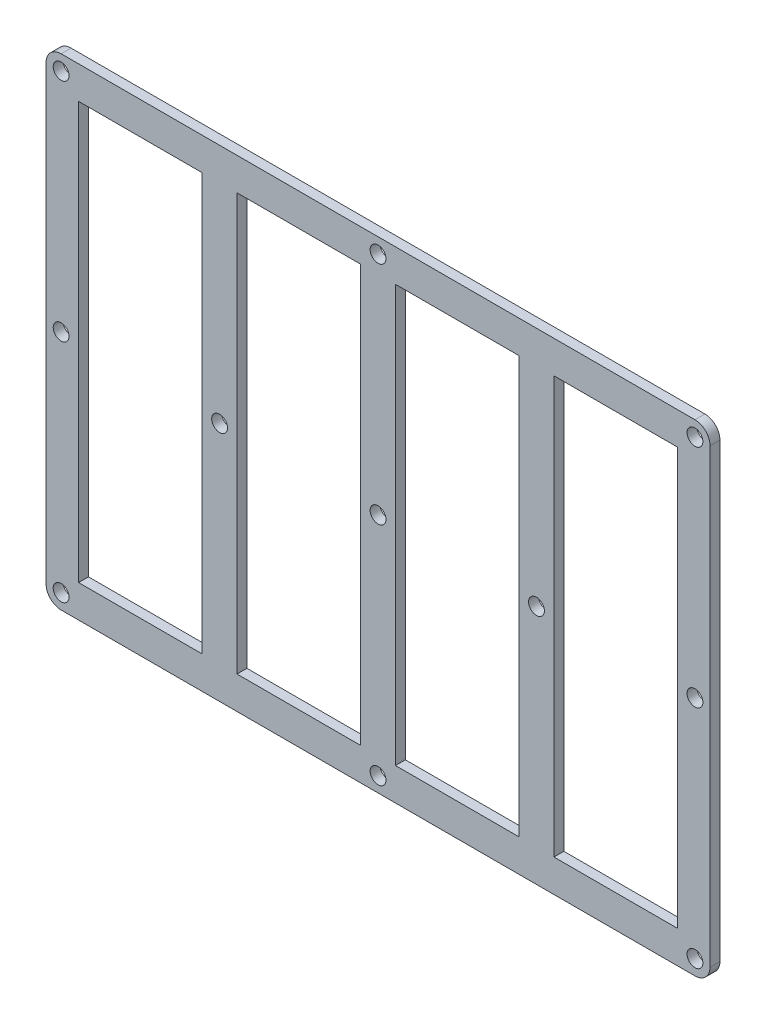
SolidWorks part; units mm, degrees
ref_plane "Front Plane" through (0, 0, 0) normal (0, 0, 1) x (1, 0, 0)
ref_plane "Top Plane" through (0, 0, 0) normal (0, 1, 0) x (1, 0, 0)
ref_plane "Right Plane" through (0, 0, 0) normal (1, 0, 0) x (0, 0, -1)
sketch "Sketch1" plane through (0, 0, 0) normal (0, 0, 1) x (1, 0, 0)
  line L0 (-152.4, 127) -> (-76.2, 127) construction
  line L1 (-152.4, 152.4) -> (152.4, 152.4)
  line L2 (-152.4, 152.4) -> (-152.4, -152.4)
  line L3 (-152.4, -152.4) -> (152.4, -152.4)
  line L4 (152.4, 152.4) -> (152.4, -152.4)
  line L5 (-76.2, 127) -> (-25.4, 127) construction
  line L6 (-25.4, 127) -> (25.4, 127) construction
  line L7 (25.4, 127) -> (76.2, 127) construction
  line L8 (76.2, 127) -> (152.4, 127) construction
  line L9 (-152.4, 0) -> (152.4, 0) construction
  line L10 (0, 152.4) -> (0, -152.4) construction
  line L11 (-118.11, 152.4) -> (-118.11, -152.4) construction
  line L12 (-152.4, -127) -> (152.4, -127) construction
  line L13 (127, 152.4) -> (127, -152.4) construction
  line L14 (-50.8, 152.4) -> (-50.8, -152.4) construction
  line L15 (50.8, 152.4) -> (50.8, -152.4) construction
  line L16 (-101.6, 152.4) -> (-101.6, -152.4) construction
  line L17 (-95.25, 66.04) -> (-57.15, 66.04) construction
  line L18 (-95.25, 66.04) -> (-95.25, -66.04) construction
  line L19 (-95.25, -66.04) -> (-57.15, -66.04) construction
  line L20 (-57.15, 66.04) -> (-57.15, -66.04) construction
  line L21 (-44.45, 66.04) -> (-6.35, 66.04) construction
  line L22 (-44.45, 66.04) -> (-44.45, -66.04) construction
  line L23 (-44.45, -66.04) -> (-6.35, -66.04) construction
  line L24 (-6.35, 66.04) -> (-6.35, -66.04) construction
  line L25 (6.35, 66.04) -> (44.45, 66.04) construction
  line L26 (6.35, 66.04) -> (6.35, -66.04) construction
  line L27 (6.35, -66.04) -> (44.45, -66.04) construction
  line L28 (44.45, 66.04) -> (44.45, -66.04) construction
  line L29 (57.15, 66.04) -> (95.25, 66.04) construction
  line L30 (57.15, 66.04) -> (57.15, -66.04) construction
  line L31 (57.15, -66.04) -> (95.25, -66.04) construction
  line L32 (95.25, 66.04) -> (95.25, -66.04) construction
  line L33 (101.6, 152.4) -> (101.6, -152.4) construction
  line L34 (-152.4, 120.65) -> (152.4, 120.65) construction
  line L35 (-101.6, 39.7057) -> (-95.25, 39.7057) construction
  line L36 (-57.15, 39.7057) -> (-50.8, 39.7057) construction
  line L37 (-76.2, 66.04) -> (-76.2, 0) construction
  line L38 (-76.2, 0) -> (-76.2, -66.04) construction
  line L39 (-152.4, 72.39) -> (152.4, 72.39) construction
  line L40 (-152.4, -72.39) -> (152.4, -72.39) construction
  line L41 (-76.2, 66.04) -> (-76.2, 72.39) construction
  line L42 (-95.25, -66.04) -> (-95.25, -72.39) construction
  line L43 (95.25, 39.7057) -> (101.6, 39.7057) construction
  line L44 (-95.25, 111.76) -> (-57.15, 111.76) construction
  line L45 (-57.15, 111.76) -> (-57.15, 118.4779) construction
  line L46 (-94.0266, 120.65) -> (-78.1749, 130.2582) construction
  line L47 (-95.25, 111.76) -> (-95.25, 118.4779) construction
  line L48 (-58.3734, 120.65) -> (-74.2251, 130.2582) construction
  line L49 (-107.3169, 130.81) -> (-83.1894, 130.81) construction
  line L50 (-6.35, 111.76) -> (-6.35, 118.4779) construction
  line L51 (-7.5734, 120.65) -> (-23.4251, 130.2582) construction
  line L52 (-43.2266, 120.65) -> (-27.3749, 130.2582) construction
  line L53 (-44.45, 111.76) -> (-44.45, 118.4779) construction
  line L54 (-6.35, 111.76) -> (-44.45, 111.76) construction
  line L55 (44.45, 111.76) -> (44.45, 118.4779) construction
  line L56 (43.2266, 120.65) -> (27.3749, 130.2582) construction
  line L57 (7.5734, 120.65) -> (23.4251, 130.2582) construction
  line L58 (6.35, 111.76) -> (6.35, 118.4779) construction
  line L59 (6.35, 111.76) -> (44.45, 111.76) construction
  line L60 (95.25, 111.76) -> (57.15, 111.76) construction
  line L61 (95.25, 111.76) -> (95.25, 118.4779) construction
  line L62 (94.0266, 120.65) -> (78.1749, 130.2582) construction
  line L63 (58.3734, 120.65) -> (74.2251, 130.2582) construction
  line L64 (57.15, 111.76) -> (57.15, 118.4779) construction
  line L65 (-95.25, -111.76) -> (-95.25, -118.4779) construction
  line L66 (-94.0266, -120.65) -> (-78.1749, -130.2582) construction
  line L67 (-58.3734, -120.65) -> (-74.2251, -130.2582) construction
  line L68 (-95.25, -111.76) -> (-57.15, -111.76) construction
  line L69 (-57.15, -111.76) -> (-57.15, -118.4779) construction
  line L70 (-44.45, -111.76) -> (-44.45, -118.4779) construction
  line L71 (-43.2266, -120.65) -> (-27.3749, -130.2582) construction
  line L72 (-6.35, -111.76) -> (-44.45, -111.76) construction
  line L73 (-7.5734, -120.65) -> (-23.4251, -130.2582) construction
  line L74 (-6.35, -111.76) -> (-6.35, -118.4779) construction
  line L75 (6.35, -111.76) -> (6.35, -118.4779) construction
  line L76 (7.5734, -120.65) -> (23.4251, -130.2582) construction
  line L77 (43.2266, -120.65) -> (27.3749, -130.2582) construction
  line L78 (6.35, -111.76) -> (44.45, -111.76) construction
  line L79 (44.45, -111.76) -> (44.45, -118.4779) construction
  line L80 (57.15, -111.76) -> (57.15, -118.4779) construction
  line L81 (58.3734, -120.65) -> (74.2251, -130.2582) construction
  line L82 (94.0266, -120.65) -> (78.1749, -130.2582) construction
  line L83 (95.25, -111.76) -> (57.15, -111.76) construction
  line L84 (95.25, -111.76) -> (95.25, -118.4779) construction
  line L85 (-152.4, 97.79) -> (152.4, 97.79) construction
  line L86 (-50.8, 39.7057) -> (-44.45, 39.7057) construction
  line L87 (-127, 152.4) -> (-127, -152.4) construction
  line L89 (-95.25, 101.6) -> (-92.3192, 101.6) construction
  line L90 (-95.25, 101.6) -> (-95.25, -101.6) construction
  line L96 (-90.8538, 101.6) -> (-90.8538, 68.58) construction
  line L97 (-89.3885, 101.6) -> (-89.3885, 68.58) construction
  line L98 (-92.3192, 101.6) -> (-92.3192, 68.58) construction
  line L99 (-83.5269, 101.6) -> (-83.5269, 68.58) construction
  line L100 (-86.4577, 101.6) -> (-86.4577, 68.58) construction
  line L101 (-89.3885, 101.6) -> (-86.4577, 101.6) construction
  line L102 (-77.6654, 101.6) -> (-77.6654, 68.58) construction
  line L103 (-80.5962, 101.6) -> (-80.5962, 68.58) construction
  line L104 (-83.5269, 101.6) -> (-80.5962, 101.6) construction
  line L105 (-71.8038, 101.6) -> (-71.8038, 68.58) construction
  line L106 (-74.7346, 101.6) -> (-74.7346, 68.58) construction
  line L107 (-77.6654, 101.6) -> (-74.7346, 101.6) construction
  line L108 (-65.9423, 101.6) -> (-65.9423, 68.58) construction
  line L109 (-68.8731, 101.6) -> (-68.8731, 68.58) construction
  line L110 (-71.8038, 101.6) -> (-68.8731, 101.6) construction
  line L111 (-60.0808, 101.6) -> (-60.0808, 68.58) construction
  line L112 (-63.0115, 101.6) -> (-63.0115, 68.58) construction
  line L113 (-65.9423, 101.6) -> (-63.0115, 101.6) construction
  line L114 (-57.15, -101.6) -> (-57.15, 101.6) construction
  line L115 (-60.0808, 101.6) -> (-57.15, 101.6) construction
  line L116 (-92.3192, 68.58) -> (-89.3885, 68.58) construction
  line L117 (-60.0808, -101.6) -> (-57.15, -101.6) construction
  line L118 (-60.0808, -101.6) -> (-60.0808, -68.58) construction
  line L119 (-63.0115, -101.6) -> (-63.0115, -68.58) construction
  line L120 (-65.9423, -101.6) -> (-65.9423, -68.58) construction
  line L121 (-65.9423, -101.6) -> (-63.0115, -101.6) construction
  line L122 (-68.8731, -101.6) -> (-68.8731, -68.58) construction
  line L123 (-71.8038, -101.6) -> (-68.8731, -101.6) construction
  line L124 (-71.8038, -101.6) -> (-71.8038, -68.58) construction
  line L125 (-74.7346, -101.6) -> (-74.7346, -68.58) construction
  line L126 (-77.6654, -101.6) -> (-74.7346, -101.6) construction
  line L127 (-77.6654, -101.6) -> (-77.6654, -68.58) construction
  line L128 (-80.5962, -101.6) -> (-80.5962, -68.58) construction
  line L129 (-83.5269, -101.6) -> (-80.5962, -101.6) construction
  line L130 (-83.5269, -101.6) -> (-83.5269, -68.58) construction
  line L131 (-86.4577, -101.6) -> (-86.4577, -68.58) construction
  line L132 (-89.3885, -101.6) -> (-86.4577, -101.6) construction
  line L133 (-89.3885, -101.6) -> (-89.3885, -68.58) construction
  line L134 (-92.3192, -101.6) -> (-92.3192, -68.58) construction
  line L135 (-95.25, -101.6) -> (-92.3192, -101.6) construction
  line L136 (-9.2808, 68.58) -> (-12.2115, 68.58) construction
  line L137 (6.35, 66.04) -> (44.45, 66.04) construction
  line L138 (-6.35, -66.04) -> (-6.35, -72.39) construction
  line L139 (-25.4, 66.04) -> (-25.4, 72.39) construction
  line L140 (-25.4, 0) -> (-25.4, -66.04) construction
  line L141 (-25.4, 66.04) -> (-25.4, 0) construction
  line L142 (-44.45, 66.04) -> (-44.45, -66.04) construction
  line L143 (-6.35, -66.04) -> (-44.45, -66.04) construction
  line L144 (-6.35, 66.04) -> (-6.35, -66.04) construction
  line L145 (-6.35, 66.04) -> (-44.45, 66.04) construction
  line L146 (-6.35, -101.6) -> (-9.2808, -101.6) construction
  line L147 (-9.2808, -101.6) -> (-9.2808, -68.58) construction
  line L148 (-12.2115, -101.6) -> (-12.2115, -68.58) construction
  line L149 (-12.2115, -101.6) -> (-15.1423, -101.6) construction
  line L150 (-15.1423, -101.6) -> (-15.1423, -68.58) construction
  line L151 (-18.0731, -101.6) -> (-18.0731, -68.58) construction
  line L152 (-18.0731, -101.6) -> (-21.0038, -101.6) construction
  line L153 (-21.0038, -101.6) -> (-21.0038, -68.58) construction
  line L154 (-23.9346, -101.6) -> (-23.9346, -68.58) construction
  line L155 (-23.9346, -101.6) -> (-26.8654, -101.6) construction
  line L156 (-26.8654, -101.6) -> (-26.8654, -68.58) construction
  line L157 (-29.7962, -101.6) -> (-29.7962, -68.58) construction
  line L158 (-29.7962, -101.6) -> (-32.7269, -101.6) construction
  line L159 (-32.7269, -101.6) -> (-32.7269, -68.58) construction
  line L160 (-35.6577, -101.6) -> (-38.5885, -101.6) construction
  line L161 (-35.6577, -101.6) -> (-35.6577, -68.58) construction
  line L162 (-38.5885, -101.6) -> (-38.5885, -68.58) construction
  line L163 (-41.5192, -101.6) -> (-41.5192, -68.58) construction
  line L164 (-41.5192, -101.6) -> (-44.45, -101.6) construction
  line L165 (-41.5192, 101.6) -> (-44.45, 101.6) construction
  line L166 (-44.45, -101.6) -> (-44.45, 101.6) construction
  line L167 (-35.6577, 101.6) -> (-38.5885, 101.6) construction
  line L168 (-38.5885, 101.6) -> (-38.5885, 68.58) construction
  line L169 (-41.5192, 101.6) -> (-41.5192, 68.58) construction
  line L170 (-29.7962, 101.6) -> (-32.7269, 101.6) construction
  line L171 (-32.7269, 101.6) -> (-32.7269, 68.58) construction
  line L172 (-35.6577, 101.6) -> (-35.6577, 68.58) construction
  line L173 (-23.9346, 101.6) -> (-26.8654, 101.6) construction
  line L174 (-26.8654, 101.6) -> (-26.8654, 68.58) construction
  line L175 (-29.7962, 101.6) -> (-29.7962, 68.58) construction
  line L176 (-18.0731, 101.6) -> (-21.0038, 101.6) construction
  line L177 (-21.0038, 101.6) -> (-21.0038, 68.58) construction
  line L178 (-23.9346, 101.6) -> (-23.9346, 68.58) construction
  line L179 (-12.2115, 101.6) -> (-15.1423, 101.6) construction
  line L180 (-15.1423, 101.6) -> (-15.1423, 68.58) construction
  line L181 (-18.0731, 101.6) -> (-18.0731, 68.58) construction
  line L182 (-9.2808, 101.6) -> (-9.2808, 68.58) construction
  line L183 (-12.2115, 101.6) -> (-12.2115, 68.58) construction
  line L184 (-6.35, 101.6) -> (-6.35, -101.6) construction
  line L185 (-6.35, 101.6) -> (-9.2808, 101.6) construction
  line L186 (6.35, 66.04) -> (6.35, -66.04) construction
  line L187 (6.35, -66.04) -> (44.45, -66.04) construction
  line L188 (44.45, 66.04) -> (44.45, -66.04) construction
  line L189 (25.4, 66.04) -> (25.4, 0) construction
  line L190 (25.4, 0) -> (25.4, -66.04) construction
  line L191 (25.4, 66.04) -> (25.4, 72.39) construction
  line L192 (6.35, -66.04) -> (6.35, -72.39) construction
  line L193 (9.2808, 68.58) -> (12.2115, 68.58) construction
  line L194 (6.35, 66.04) -> (6.35, -66.04) construction
  line L195 (44.45, -66.04) -> (6.35, -66.04) construction
  line L196 (44.45, 66.04) -> (44.45, -66.04) construction
  line L197 (44.45, 66.04) -> (6.35, 66.04) construction
  line L198 (6.35, 101.6) -> (9.2808, 101.6) construction
  line L199 (6.35, 101.6) -> (6.35, -101.6) construction
  line L200 (12.2115, 101.6) -> (12.2115, 68.58) construction
  line L201 (9.2808, 101.6) -> (9.2808, 68.58) construction
  line L202 (18.0731, 101.6) -> (18.0731, 68.58) construction
  line L203 (15.1423, 101.6) -> (15.1423, 68.58) construction
  line L204 (12.2115, 101.6) -> (15.1423, 101.6) construction
  line L205 (23.9346, 101.6) -> (23.9346, 68.58) construction
  line L206 (21.0038, 101.6) -> (21.0038, 68.58) construction
  line L207 (18.0731, 101.6) -> (21.0038, 101.6) construction
  line L208 (29.7962, 101.6) -> (29.7962, 68.58) construction
  line L209 (26.8654, 101.6) -> (26.8654, 68.58) construction
  line L210 (23.9346, 101.6) -> (26.8654, 101.6) construction
  line L211 (35.6577, 101.6) -> (35.6577, 68.58) construction
  line L212 (32.7269, 101.6) -> (32.7269, 68.58) construction
  line L213 (29.7962, 101.6) -> (32.7269, 101.6) construction
  line L214 (41.5192, 101.6) -> (41.5192, 68.58) construction
  line L215 (38.5885, 101.6) -> (38.5885, 68.58) construction
  line L216 (35.6577, 101.6) -> (38.5885, 101.6) construction
  line L217 (44.45, -101.6) -> (44.45, 101.6) construction
  line L218 (41.5192, 101.6) -> (44.45, 101.6) construction
  line L219 (41.5192, -101.6) -> (44.45, -101.6) construction
  line L220 (41.5192, -101.6) -> (41.5192, -68.58) construction
  line L221 (38.5885, -101.6) -> (38.5885, -68.58) construction
  line L222 (35.6577, -101.6) -> (35.6577, -68.58) construction
  line L223 (35.6577, -101.6) -> (38.5885, -101.6) construction
  line L224 (32.7269, -101.6) -> (32.7269, -68.58) construction
  line L225 (29.7962, -101.6) -> (32.7269, -101.6) construction
  line L226 (29.7962, -101.6) -> (29.7962, -68.58) construction
  line L227 (26.8654, -101.6) -> (26.8654, -68.58) construction
  line L228 (23.9346, -101.6) -> (26.8654, -101.6) construction
  line L229 (23.9346, -101.6) -> (23.9346, -68.58) construction
  line L230 (21.0038, -101.6) -> (21.0038, -68.58) construction
  line L231 (18.0731, -101.6) -> (21.0038, -101.6) construction
  line L232 (18.0731, -101.6) -> (18.0731, -68.58) construction
  line L233 (15.1423, -101.6) -> (15.1423, -68.58) construction
  line L234 (12.2115, -101.6) -> (15.1423, -101.6) construction
  line L235 (12.2115, -101.6) -> (12.2115, -68.58) construction
  line L236 (9.2808, -101.6) -> (9.2808, -68.58) construction
  line L237 (6.35, -101.6) -> (9.2808, -101.6) construction
  line L238 (57.15, 66.04) -> (95.25, 66.04) construction
  line L239 (57.15, 66.04) -> (57.15, -66.04) construction
  line L240 (57.15, -66.04) -> (95.25, -66.04) construction
  line L241 (95.25, 66.04) -> (95.25, -66.04) construction
  line L242 (92.3192, 68.58) -> (89.3885, 68.58) construction
  line L243 (95.25, -66.04) -> (95.25, -72.39) construction
  line L244 (76.2, 66.04) -> (76.2, 72.39) construction
  line L245 (76.2, 0) -> (76.2, -66.04) construction
  line L246 (76.2, 66.04) -> (76.2, 0) construction
  line L247 (57.15, 66.04) -> (57.15, -66.04) construction
  line L248 (95.25, -66.04) -> (57.15, -66.04) construction
  line L249 (95.25, 66.04) -> (95.25, -66.04) construction
  line L250 (95.25, 66.04) -> (57.15, 66.04) construction
  line L251 (57.15, 66.04) -> (57.15, -66.04) construction
  line L252 (95.25, -66.04) -> (57.15, -66.04) construction
  line L253 (95.25, 66.04) -> (95.25, -66.04) construction
  line L254 (95.25, 66.04) -> (57.15, 66.04) construction
  line L255 (95.25, -101.6) -> (92.3192, -101.6) construction
  line L256 (92.3192, -101.6) -> (92.3192, -68.58) construction
  line L257 (89.3885, -101.6) -> (89.3885, -68.58) construction
  line L258 (89.3885, -101.6) -> (86.4577, -101.6) construction
  line L259 (86.4577, -101.6) -> (86.4577, -68.58) construction
  line L260 (83.5269, -101.6) -> (83.5269, -68.58) construction
  line L261 (83.5269, -101.6) -> (80.5962, -101.6) construction
  line L262 (80.5962, -101.6) -> (80.5962, -68.58) construction
  line L263 (77.6654, -101.6) -> (77.6654, -68.58) construction
  line L264 (77.6654, -101.6) -> (74.7346, -101.6) construction
  line L265 (74.7346, -101.6) -> (74.7346, -68.58) construction
  line L266 (71.8038, -101.6) -> (71.8038, -68.58) construction
  line L267 (71.8038, -101.6) -> (68.8731, -101.6) construction
  line L268 (68.8731, -101.6) -> (68.8731, -68.58) construction
  line L269 (65.9423, -101.6) -> (63.0115, -101.6) construction
  line L270 (65.9423, -101.6) -> (65.9423, -68.58) construction
  line L271 (63.0115, -101.6) -> (63.0115, -68.58) construction
  line L272 (60.0808, -101.6) -> (60.0808, -68.58) construction
  line L273 (60.0808, -101.6) -> (57.15, -101.6) construction
  line L274 (60.0808, 101.6) -> (57.15, 101.6) construction
  line L275 (57.15, -101.6) -> (57.15, 101.6) construction
  line L276 (65.9423, 101.6) -> (63.0115, 101.6) construction
  line L277 (63.0115, 101.6) -> (63.0115, 68.58) construction
  line L278 (60.0808, 101.6) -> (60.0808, 68.58) construction
  line L279 (71.8038, 101.6) -> (68.8731, 101.6) construction
  line L280 (68.8731, 101.6) -> (68.8731, 68.58) construction
  line L281 (65.9423, 101.6) -> (65.9423, 68.58) construction
  line L282 (77.6654, 101.6) -> (74.7346, 101.6) construction
  line L283 (74.7346, 101.6) -> (74.7346, 68.58) construction
  line L284 (71.8038, 101.6) -> (71.8038, 68.58) construction
  line L285 (83.5269, 101.6) -> (80.5962, 101.6) construction
  line L286 (80.5962, 101.6) -> (80.5962, 68.58) construction
  line L287 (77.6654, 101.6) -> (77.6654, 68.58) construction
  line L288 (89.3885, 101.6) -> (86.4577, 101.6) construction
  line L289 (86.4577, 101.6) -> (86.4577, 68.58) construction
  line L290 (83.5269, 101.6) -> (83.5269, 68.58) construction
  line L291 (92.3192, 101.6) -> (92.3192, 68.58) construction
  line L292 (89.3885, 101.6) -> (89.3885, 68.58) construction
  line L293 (95.25, 101.6) -> (95.25, -101.6) construction
  line L294 (95.25, 101.6) -> (92.3192, 101.6) construction
  line L295 (-101.6, 39.7057) -> (-107.95, 39.7057) construction
  line L296 (-101.6, 78.74) -> (101.6, 78.74)
  line L298 (-101.6, -78.74) -> (101.6, -78.74)
  line L300 (-97.0611, 78.74) -> (-97.0611, 72.39) construction
  line L301 (-110.49, 22.225) -> (-120.65, 22.225) construction
  line L302 (-127, 15.875) -> (-127, -15.875) construction
  line L303 (-120.65, -22.225) -> (-110.49, -22.225) construction
  line L304 (-90.964, 120.65) -> (-61.436, 120.65) construction
  line L305 (-90.964, 122.2375) -> (-61.436, 122.2375) construction
  line L306 (-90.964, 119.0625) -> (-61.436, 119.0625) construction
  line L307 (-10.636, 120.65) -> (-40.164, 120.65) construction
  line L308 (-10.636, 122.2375) -> (-40.164, 122.2375) construction
  line L309 (-10.636, 119.0625) -> (-40.164, 119.0625) construction
  line L310 (10.636, 120.65) -> (40.164, 120.65) construction
  line L311 (10.636, 122.2375) -> (40.164, 122.2375) construction
  line L312 (10.636, 119.0625) -> (40.164, 119.0625) construction
  line L313 (90.964, 120.65) -> (61.436, 120.65) construction
  line L314 (90.964, 122.2375) -> (61.436, 122.2375) construction
  line L315 (90.964, 119.0625) -> (61.436, 119.0625) construction
  line L316 (90.964, -120.65) -> (61.436, -120.65) construction
  line L317 (90.964, -122.2375) -> (61.436, -122.2375) construction
  line L318 (90.964, -119.0625) -> (61.436, -119.0625) construction
  line L319 (10.636, -120.65) -> (40.164, -120.65) construction
  line L320 (10.636, -122.2375) -> (40.164, -122.2375) construction
  line L321 (10.636, -119.0625) -> (40.164, -119.0625) construction
  line L322 (-10.636, -120.65) -> (-40.164, -120.65) construction
  line L323 (-10.636, -122.2375) -> (-40.164, -122.2375) construction
  line L324 (-10.636, -119.0625) -> (-40.164, -119.0625) construction
  line L325 (-90.964, -120.65) -> (-61.436, -120.65) construction
  line L326 (-90.964, -122.2375) -> (-61.436, -122.2375) construction
  line L327 (-90.964, -119.0625) -> (-61.436, -119.0625) construction
  line L328 (-6.35, 111.125) -> (-6.35, 92.075) construction
  line L329 (-95.25, 111.125) -> (-57.15, 111.125) construction
  line L330 (-95.25, 111.125) -> (-95.25, 92.075) construction
  line L331 (-95.25, 92.075) -> (-57.15, 92.075) construction
  line L332 (-57.15, 111.125) -> (-57.15, 92.075) construction
  line L333 (-6.35, 111.125) -> (-44.45, 111.125) construction
  line L334 (-44.45, 111.125) -> (-44.45, 92.075) construction
  line L335 (-6.35, 92.075) -> (-44.45, 92.075) construction
  line L336 (95.25, 92.075) -> (57.15, 92.075) construction
  line L337 (95.25, 111.125) -> (95.25, 92.075)
  line L338 (95.25, 111.125) -> (57.15, 111.125) construction
  line L339 (57.15, 111.125) -> (57.15, 92.075) construction
  line L340 (44.45, 111.125) -> (44.45, 92.075) construction
  line L341 (6.35, 92.075) -> (44.45, 92.075) construction
  line L342 (6.35, 111.125) -> (44.45, 111.125) construction
  line L343 (6.35, 111.125) -> (6.35, 92.075) construction
  line L344 (-95.25, -92.075) -> (-57.15, -92.075) construction
  line L345 (-95.25, -111.125) -> (-95.25, -92.075) construction
  line L346 (-95.25, -111.125) -> (-57.15, -111.125) construction
  line L347 (-57.15, -111.125) -> (-57.15, -92.075) construction
  line L348 (-44.45, -111.125) -> (-44.45, -92.075) construction
  line L349 (-6.35, -92.075) -> (-44.45, -92.075) construction
  line L350 (-6.35, -111.125) -> (-44.45, -111.125) construction
  line L351 (-6.35, -111.125) -> (-6.35, -92.075) construction
  line L352 (6.35, -111.125) -> (6.35, -92.075) construction
  line L353 (6.35, -92.075) -> (44.45, -92.075) construction
  line L354 (6.35, -111.125) -> (44.45, -111.125) construction
  line L355 (44.45, -111.125) -> (44.45, -92.075) construction
  line L356 (57.15, -111.125) -> (57.15, -92.075) construction
  line L357 (95.25, -111.125) -> (57.15, -111.125) construction
  line L358 (95.25, -111.125) -> (95.25, -92.075) construction
  line L359 (95.25, -92.075) -> (57.15, -92.075) construction
  line L360 (-107.95, 72.39) -> (-107.95, 24.765)
  line L361 (-107.95, 22.225) -> (-107.95, -22.225) construction
  line L362 (-107.95, -24.765) -> (-107.95, -72.39)
  line L363 (3.659, 78.74) -> (3.659, -78.74) construction
  line L364 (120.65, -22.225) -> (110.49, -22.225) construction
  line L365 (127, 15.875) -> (127, -15.875) construction
  line L366 (110.49, 22.225) -> (120.65, 22.225) construction
  line L367 (107.95, 72.39) -> (107.95, 24.765)
  line L368 (107.95, -24.765) -> (107.95, -72.39)
  line L369 (-107.95, 24.765) -> (-107.95, -24.765)
  line L370 (107.95, 24.765) -> (107.95, -24.765)
  line L371 (-101.6, 77.978) -> (101.6, 77.978) construction
  line L372 (107.188, 72.39) -> (107.188, 24.765) construction
  line L373 (107.188, 24.765) -> (107.188, -24.765) construction
  line L374 (107.188, -24.765) -> (107.188, -72.39) construction
  line L375 (-101.6, -77.978) -> (101.6, -77.978) construction
  line L376 (-107.188, -24.765) -> (-107.188, -72.39) construction
  line L377 (-107.188, 24.765) -> (-107.188, -24.765) construction
  line L378 (-107.188, 72.39) -> (-107.188, 24.765) construction
  line L379 (-96.012, 66.802) -> (-56.388, 66.802)
  line L380 (-56.388, 66.802) -> (-56.388, -66.802)
  line L381 (-96.012, -66.802) -> (-56.388, -66.802)
  line L382 (-96.012, 66.802) -> (-96.012, -66.802)
  line L383 (-45.212, 66.802) -> (-45.212, -66.802)
  line L384 (-45.212, -66.802) -> (-5.588, -66.802)
  line L385 (-5.588, 66.802) -> (-5.588, -66.802)
  line L386 (-45.212, 66.802) -> (-5.588, 66.802)
  line L387 (5.588, 66.802) -> (45.212, 66.802)
  line L388 (45.212, 66.802) -> (45.212, -66.802)
  line L389 (5.588, -66.802) -> (45.212, -66.802)
  line L390 (5.588, 66.802) -> (5.588, -66.802)
  line L391 (56.388, 66.802) -> (96.012, 66.802)
  line L392 (96.012, 66.802) -> (96.012, -66.802)
  line L393 (56.388, -66.802) -> (96.012, -66.802)
  line L394 (56.388, 66.802) -> (56.388, -66.802)
  line L395 (106.426, 72.39) -> (106.426, 24.765)
  line L396 (106.426, 24.765) -> (106.426, -24.765)
  line L397 (106.426, -24.765) -> (106.426, -72.39)
  line L398 (-101.6, -77.216) -> (101.6, -77.216)
  line L399 (-106.426, -24.765) -> (-106.426, -72.39)
  line L400 (-106.426, 24.765) -> (-106.426, -24.765)
  line L401 (-106.426, 72.39) -> (-106.426, 24.765)
  line L402 (-101.6, 77.216) -> (101.6, 77.216)
  circle A0 centre (-76.2, 127) radius 2.5527 construction
  circle A1 centre (-25.4, 127) radius 2.5527 construction
  circle A2 centre (25.4, 127) radius 2.5527 construction
  circle A3 centre (76.2, 127) radius 2.5527 construction
  circle A4 centre (-101.6, 0) radius 2.54
  circle A5 centre (-50.8, 0) radius 2.54
  circle A6 centre (0, 0) radius 2.54
  circle A7 centre (101.6, 0) radius 2.54
  circle A8 centre (50.8, 0) radius 2.54
  circle A9 centre (-50.8, 127) radius 2.54
  circle A10 centre (0, 127) radius 2.54
  circle A11 centre (50.8, 127) radius 2.54
  circle A12 centre (-101.6, 72.39) radius 2.54
  circle A13 centre (0, 72.39) radius 2.54
  circle A14 centre (101.6, 72.39) radius 2.54
  circle A15 centre (-101.6, -72.39) radius 2.54
  circle A16 centre (0, -72.39) radius 2.54
  circle A17 centre (101.6, -72.39) radius 2.54
  arc A18 (-74.2251, 130.2582) -> (-78.1749, 130.2582) centre (-76.2, 127) ccw construction
  arc A19 (-57.15, 118.4779) -> (-58.3734, 120.65) centre (-59.69, 118.4779) ccw construction
  arc A20 (-95.25, 118.4779) -> (-94.0266, 120.65) centre (-92.71, 118.4779) cw construction
  arc A21 (-6.35, 118.4779) -> (-7.5734, 120.65) centre (-8.89, 118.4779) ccw construction
  arc A22 (-27.3749, 130.2582) -> (-23.4251, 130.2582) centre (-25.4, 127) cw construction
  arc A23 (-44.45, 118.4779) -> (-43.2266, 120.65) centre (-41.91, 118.4779) cw construction
  arc A24 (44.45, 118.4779) -> (43.2266, 120.65) centre (41.91, 118.4779) ccw construction
  arc A25 (27.3749, 130.2582) -> (23.4251, 130.2582) centre (25.4, 127) ccw construction
  arc A26 (6.35, 118.4779) -> (7.5734, 120.65) centre (8.89, 118.4779) cw construction
  arc A27 (95.25, 118.4779) -> (94.0266, 120.65) centre (92.71, 118.4779) ccw construction
  arc A28 (74.2251, 130.2582) -> (78.1749, 130.2582) centre (76.2, 127) cw construction
  arc A29 (57.15, 118.4779) -> (58.3734, 120.65) centre (59.69, 118.4779) cw construction
  circle A30 centre (-76.2, -127) radius 2.5527 construction
  circle A31 centre (-25.4, -127) radius 2.5527 construction
  circle A32 centre (25.4, -127) radius 2.5527 construction
  circle A33 centre (76.2, -127) radius 2.5527 construction
  arc A34 (-95.25, -118.4779) -> (-94.0266, -120.65) centre (-92.71, -118.4779) ccw construction
  arc A35 (-74.2251, -130.2582) -> (-78.1749, -130.2582) centre (-76.2, -127) cw construction
  arc A36 (-57.15, -118.4779) -> (-58.3734, -120.65) centre (-59.69, -118.4779) cw construction
  arc A37 (-44.45, -118.4779) -> (-43.2266, -120.65) centre (-41.91, -118.4779) ccw construction
  arc A38 (-27.3749, -130.2582) -> (-23.4251, -130.2582) centre (-25.4, -127) ccw construction
  arc A39 (-6.35, -118.4779) -> (-7.5734, -120.65) centre (-8.89, -118.4779) cw construction
  arc A40 (6.35, -118.4779) -> (7.5734, -120.65) centre (8.89, -118.4779) ccw construction
  arc A41 (27.3749, -130.2582) -> (23.4251, -130.2582) centre (25.4, -127) cw construction
  arc A42 (44.45, -118.4779) -> (43.2266, -120.65) centre (41.91, -118.4779) cw construction
  arc A43 (57.15, -118.4779) -> (58.3734, -120.65) centre (59.69, -118.4779) ccw construction
  arc A44 (74.2251, -130.2582) -> (78.1749, -130.2582) centre (76.2, -127) ccw construction
  arc A45 (95.25, -118.4779) -> (94.0266, -120.65) centre (92.71, -118.4779) cw construction
  circle A46 centre (50.8, -127) radius 2.54
  circle A47 centre (0, -127) radius 2.54
  circle A48 centre (-50.8, -127) radius 2.54
  circle A49 centre (-101.6, 97.79) radius 2.54
  circle A50 centre (0, 97.79) radius 2.54
  circle A51 centre (101.6, 97.79) radius 2.54
  circle A52 centre (101.6, 127) radius 2.54
  circle A53 centre (-101.6, 127) radius 2.54
  circle A54 centre (-118.11, 33.02) radius 2.54
  circle A55 centre (127, 33.02) radius 2.54
  circle A56 centre (-101.6, -127) radius 2.54
  circle A57 centre (101.6, -127) radius 2.54
  circle A58 centre (101.6, -97.79) radius 2.54
  circle A59 centre (0, -97.79) radius 2.54
  circle A60 centre (-101.6, -97.79) radius 2.54
  circle A61 centre (-118.11, -33.02) radius 2.54
  circle A62 centre (127, -33.02) radius 2.54
  circle A63 centre (-139.7, 139.7) radius 3.2639
  circle A64 centre (-139.7, 0) radius 3.2639
  circle A65 centre (-139.7, -139.7) radius 3.2639
  circle A66 centre (139.7, -139.7) radius 3.2639
  circle A67 centre (139.7, 0) radius 3.2639
  circle A68 centre (139.7, 139.7) radius 3.2639
  arc A70 (-92.3192, 68.58) -> (-89.3885, 68.58) centre (-90.8538, 68.58) ccw construction
  arc A71 (-86.4577, 68.58) -> (-83.5269, 68.58) centre (-84.9923, 68.58) ccw construction
  arc A72 (-80.5962, 68.58) -> (-77.6654, 68.58) centre (-79.1308, 68.58) ccw construction
  arc A73 (-74.7346, 68.58) -> (-71.8038, 68.58) centre (-73.2692, 68.58) ccw construction
  arc A74 (-68.8731, 68.58) -> (-65.9423, 68.58) centre (-67.4077, 68.58) ccw construction
  arc A75 (-63.0115, 68.58) -> (-60.0808, 68.58) centre (-61.5462, 68.58) ccw construction
  arc A76 (-63.0115, -68.58) -> (-60.0808, -68.58) centre (-61.5462, -68.58) cw construction
  arc A77 (-68.8731, -68.58) -> (-65.9423, -68.58) centre (-67.4077, -68.58) cw construction
  arc A78 (-74.7346, -68.58) -> (-71.8038, -68.58) centre (-73.2692, -68.58) cw construction
  arc A79 (-80.5962, -68.58) -> (-77.6654, -68.58) centre (-79.1308, -68.58) cw construction
  arc A80 (-86.4577, -68.58) -> (-83.5269, -68.58) centre (-84.9923, -68.58) cw construction
  arc A81 (-92.3192, -68.58) -> (-89.3885, -68.58) centre (-90.8538, -68.58) cw construction
  arc A82 (-9.2808, -68.58) -> (-12.2115, -68.58) centre (-10.7462, -68.58) ccw construction
  arc A83 (-15.1423, -68.58) -> (-18.0731, -68.58) centre (-16.6077, -68.58) ccw construction
  arc A84 (-21.0038, -68.58) -> (-23.9346, -68.58) centre (-22.4692, -68.58) ccw construction
  arc A85 (-26.8654, -68.58) -> (-29.7962, -68.58) centre (-28.3308, -68.58) ccw construction
  arc A86 (-32.7269, -68.58) -> (-35.6577, -68.58) centre (-34.1923, -68.58) ccw construction
  arc A87 (-38.5885, -68.58) -> (-41.5192, -68.58) centre (-40.0538, -68.58) ccw construction
  arc A88 (-38.5885, 68.58) -> (-41.5192, 68.58) centre (-40.0538, 68.58) cw construction
  arc A89 (-32.7269, 68.58) -> (-35.6577, 68.58) centre (-34.1923, 68.58) cw construction
  arc A90 (-26.8654, 68.58) -> (-29.7962, 68.58) centre (-28.3308, 68.58) cw construction
  arc A91 (-21.0038, 68.58) -> (-23.9346, 68.58) centre (-22.4692, 68.58) cw construction
  arc A92 (-15.1423, 68.58) -> (-18.0731, 68.58) centre (-16.6077, 68.58) cw construction
  arc A93 (-9.2808, 68.58) -> (-12.2115, 68.58) centre (-10.7462, 68.58) cw construction
  arc A94 (9.2808, 68.58) -> (12.2115, 68.58) centre (10.7462, 68.58) ccw construction
  arc A95 (15.1423, 68.58) -> (18.0731, 68.58) centre (16.6077, 68.58) ccw construction
  arc A96 (21.0038, 68.58) -> (23.9346, 68.58) centre (22.4692, 68.58) ccw construction
  arc A97 (26.8654, 68.58) -> (29.7962, 68.58) centre (28.3308, 68.58) ccw construction
  arc A98 (32.7269, 68.58) -> (35.6577, 68.58) centre (34.1923, 68.58) ccw construction
  arc A99 (38.5885, 68.58) -> (41.5192, 68.58) centre (40.0538, 68.58) ccw construction
  arc A100 (38.5885, -68.58) -> (41.5192, -68.58) centre (40.0538, -68.58) cw construction
  arc A101 (32.7269, -68.58) -> (35.6577, -68.58) centre (34.1923, -68.58) cw construction
  arc A102 (26.8654, -68.58) -> (29.7962, -68.58) centre (28.3308, -68.58) cw construction
  arc A103 (21.0038, -68.58) -> (23.9346, -68.58) centre (22.4692, -68.58) cw construction
  arc A104 (15.1423, -68.58) -> (18.0731, -68.58) centre (16.6077, -68.58) cw construction
  arc A105 (9.2808, -68.58) -> (12.2115, -68.58) centre (10.7462, -68.58) cw construction
  arc A106 (92.3192, -68.58) -> (89.3885, -68.58) centre (90.8538, -68.58) ccw construction
  arc A107 (86.4577, -68.58) -> (83.5269, -68.58) centre (84.9923, -68.58) ccw construction
  arc A108 (80.5962, -68.58) -> (77.6654, -68.58) centre (79.1308, -68.58) ccw construction
  arc A109 (74.7346, -68.58) -> (71.8038, -68.58) centre (73.2692, -68.58) ccw construction
  arc A110 (68.8731, -68.58) -> (65.9423, -68.58) centre (67.4077, -68.58) ccw construction
  arc A111 (63.0115, -68.58) -> (60.0808, -68.58) centre (61.5462, -68.58) ccw construction
  arc A112 (63.0115, 68.58) -> (60.0808, 68.58) centre (61.5462, 68.58) cw construction
  arc A113 (68.8731, 68.58) -> (65.9423, 68.58) centre (67.4077, 68.58) cw construction
  arc A114 (74.7346, 68.58) -> (71.8038, 68.58) centre (73.2692, 68.58) cw construction
  arc A115 (80.5962, 68.58) -> (77.6654, 68.58) centre (79.1308, 68.58) cw construction
  arc A116 (86.4577, 68.58) -> (83.5269, 68.58) centre (84.9923, 68.58) cw construction
  arc A117 (92.3192, 68.58) -> (89.3885, 68.58) centre (90.8538, 68.58) cw construction
  arc A118 (-101.6, 78.74) -> (-107.95, 72.39) centre (-101.6, 72.39) ccw
  arc A119 (-107.95, -72.39) -> (-101.6, -78.74) centre (-101.6, -72.39) ccw
  arc A120 (101.6, 78.74) -> (107.95, 72.39) centre (101.6, 72.39) cw
  arc A121 (101.6, -78.74) -> (107.95, -72.39) centre (101.6, -72.39) ccw
  arc A122 (-127, -15.875) -> (-120.65, -22.225) centre (-120.65, -15.875) ccw construction
  arc A123 (-120.65, 22.225) -> (-127, 15.875) centre (-120.65, 15.875) ccw construction
  arc A124 (-90.964, 122.2375) -> (-90.964, 119.0625) centre (-90.964, 120.65) ccw construction
  arc A125 (-61.436, 119.0625) -> (-61.436, 122.2375) centre (-61.436, 120.65) ccw construction
  arc A126 (-10.636, 122.2375) -> (-10.636, 119.0625) centre (-10.636, 120.65) cw construction
  arc A127 (-40.164, 119.0625) -> (-40.164, 122.2375) centre (-40.164, 120.65) cw construction
  arc A128 (10.636, 122.2375) -> (10.636, 119.0625) centre (10.636, 120.65) ccw construction
  arc A129 (40.164, 119.0625) -> (40.164, 122.2375) centre (40.164, 120.65) ccw construction
  arc A130 (90.964, 122.2375) -> (90.964, 119.0625) centre (90.964, 120.65) cw construction
  arc A131 (61.436, 119.0625) -> (61.436, 122.2375) centre (61.436, 120.65) cw construction
  arc A132 (90.964, -122.2375) -> (90.964, -119.0625) centre (90.964, -120.65) ccw construction
  arc A133 (61.436, -119.0625) -> (61.436, -122.2375) centre (61.436, -120.65) ccw construction
  arc A134 (10.636, -122.2375) -> (10.636, -119.0625) centre (10.636, -120.65) cw construction
  arc A135 (40.164, -119.0625) -> (40.164, -122.2375) centre (40.164, -120.65) cw construction
  arc A136 (-10.636, -122.2375) -> (-10.636, -119.0625) centre (-10.636, -120.65) ccw construction
  arc A137 (-40.164, -119.0625) -> (-40.164, -122.2375) centre (-40.164, -120.65) ccw construction
  arc A138 (-90.964, -122.2375) -> (-90.964, -119.0625) centre (-90.964, -120.65) cw construction
  arc A139 (-61.436, -119.0625) -> (-61.436, -122.2375) centre (-61.436, -120.65) cw construction
  arc A140 (-110.49, -22.225) -> (-107.95, -24.765) centre (-110.49, -24.765) cw construction
  arc A141 (-110.49, 22.225) -> (-107.95, 24.765) centre (-110.49, 24.765) ccw construction
  arc A142 (110.49, -22.225) -> (107.95, -24.765) centre (110.49, -24.765) ccw construction
  arc A143 (127, -15.875) -> (120.65, -22.225) centre (120.65, -15.875) cw construction
  arc A144 (120.65, 22.225) -> (127, 15.875) centre (120.65, 15.875) cw construction
  arc A145 (110.49, 22.225) -> (107.95, 24.765) centre (110.49, 24.765) cw construction
  arc A146 (101.6, 77.978) -> (107.188, 72.39) centre (101.6, 72.39) cw construction
  arc A147 (101.6, -77.978) -> (107.188, -72.39) centre (101.6, -72.39) ccw construction
  arc A148 (-107.188, -72.39) -> (-101.6, -77.978) centre (-101.6, -72.39) ccw construction
  arc A149 (-101.6, 77.978) -> (-107.188, 72.39) centre (-101.6, 72.39) ccw construction
  arc A150 (101.6, -77.216) -> (106.426, -72.39) centre (101.6, -72.39) ccw
  arc A151 (-106.426, -72.39) -> (-101.6, -77.216) centre (-101.6, -72.39) ccw
  arc A152 (-101.6, 77.216) -> (-106.426, 72.39) centre (-101.6, 72.39) ccw
  arc A153 (101.6, 77.216) -> (106.426, 72.39) centre (101.6, 72.39) cw
  point P10 (-76.2, 111.76)
  point P63 (50.8, 127)
  point P95 (-76.2, 66.04)
  point P97 (-25.4, 66.04)
  point P99 (25.4, 66.04)
  point P101 (76.2, 66.04)
  point P116 (-95.25, 0)
  point P118 (-44.45, 0)
  point P119 (6.35, 0)
  point P120 (57.15, 0)
  point P219 (-76.2, 33.02)
  point P259 (0, 78.74)
  point P260 (3.659, 0)
  point P545 (-127, 0)
  point P548 (-127, -22.225)
  point P551 (-127, 22.225)
  point P554 (-76.2, 120.65)
  point P562 (-25.4, 120.65)
  point P569 (25.4, 120.65)
  point P576 (76.2, 120.65)
  point P583 (76.2, -120.65)
  point P590 (25.4, -120.65)
  point P597 (-25.4, -120.65)
  point P604 (-76.2, -120.65)
  point P612 (-57.15, 101.6)
  point P613 (-58.6154, 101.6)
  dimension "D1" = 5.1054
  dimension "D7" = 5.08
  dimension "D11" = 7.62
  dimension "D13" = 2.54
  dimension "D19" = 6.5278
  dimension "D25" = 6.35
  dimension "D26" = 6.35
  dimension "D27" = 6.35
  dimension "D29" = 6.35
  dimension "D32" = 2.54
  dimension "D2" = 25.4
  dimension "D3" = 50.8
  dimension "D4" = 25.4
  dimension "D5" = 25.4
  dimension "D6" = 25.4
  dimension "D8" = 38.1
  dimension "D9" = 31.75
  dimension "D10" = 132.08
  dimension "D12" = 19.05
  dimension "D14" = 25.4
  dimension "D15" = 304.8
  dimension "D16" = 304.8
  dimension "D17" = 8.89
  dimension "D18" = 12.7
  dimension "D20" = 12.7
  dimension "D21" = 12.7
  dimension "D23" = 33.02
  dimension "D24" = 10.16
  dimension "D28" = 44.45
  dimension "D30" = 3.175
  dimension "D31" = 19.05
  dimension "D33" = 0.762
  dimension "D34" = 0.762
  dimension "D35" = 0.762
  dimension "D36" = 0.762
  dimension "D37" = 0.762
  dimension "D38" = 0.762
  dimension "D22" = 6
extrude "Boss-Extrude1" add sketch "Sketch1" along normal blind 3.175 contours L371 A149 L378 L377 L376 A148 L375 A147 L374 L373 L372 A146 A4 A5 A6 A7 A8 A12 A13 A14 A15 A16 A17
